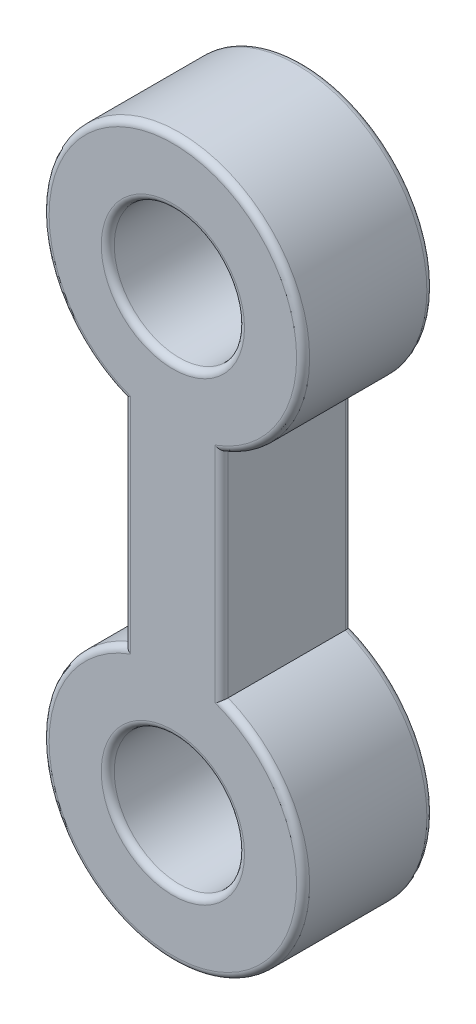
SolidWorks part; units mm, degrees
ref_plane "Front Plane" through (0, 0, 0) normal (0, 0, 1) x (1, 0, 0)
ref_plane "Top Plane" through (0, 0, 0) normal (0, 1, 0) x (1, 0, 0)
ref_plane "Right Plane" through (0, 0, 0) normal (1, 0, 0) x (0, 0, -1)
sketch "Sketch1" plane through (0, 0, 0) normal (0, 0, 1) x (1, 0, 0)
  line L0 (-7.5, -18.5405) -> (-7.5, -51.4595)
  line L1 (0, 0) -> (0, -70) construction
  line L2 (7.5, -18.5405) -> (7.5, -51.4595)
  circle A0 centre (0, 0) radius 10
  arc A1 (7.5, -18.5405) -> (-7.5, -18.5405) centre (0, 0) ccw
  arc A2 (-7.5, -51.4595) -> (7.5, -51.4595) centre (0, -70) ccw
  circle A3 centre (0, -70) radius 10
  dimension "D1" = 40
  dimension "D2" = 20
  dimension "D3" = 70
  dimension "D4" = 15
extrude "Boss-Extrude1" add sketch "Sketch1" along normal mid plane 20
fillet "Fillet1" radius 1 12 edges at (10, -70, -10) (10, 0, -10) (-7.5, -35, -10) (0, -90, -10) (7.5, -35, -10) (0, 20, -10) (10, -70, 10) (7.5, -35, 10) (0, -90, 10) (-7.5, -35, 10) (0, 20, 10) (10, 0, 10)
